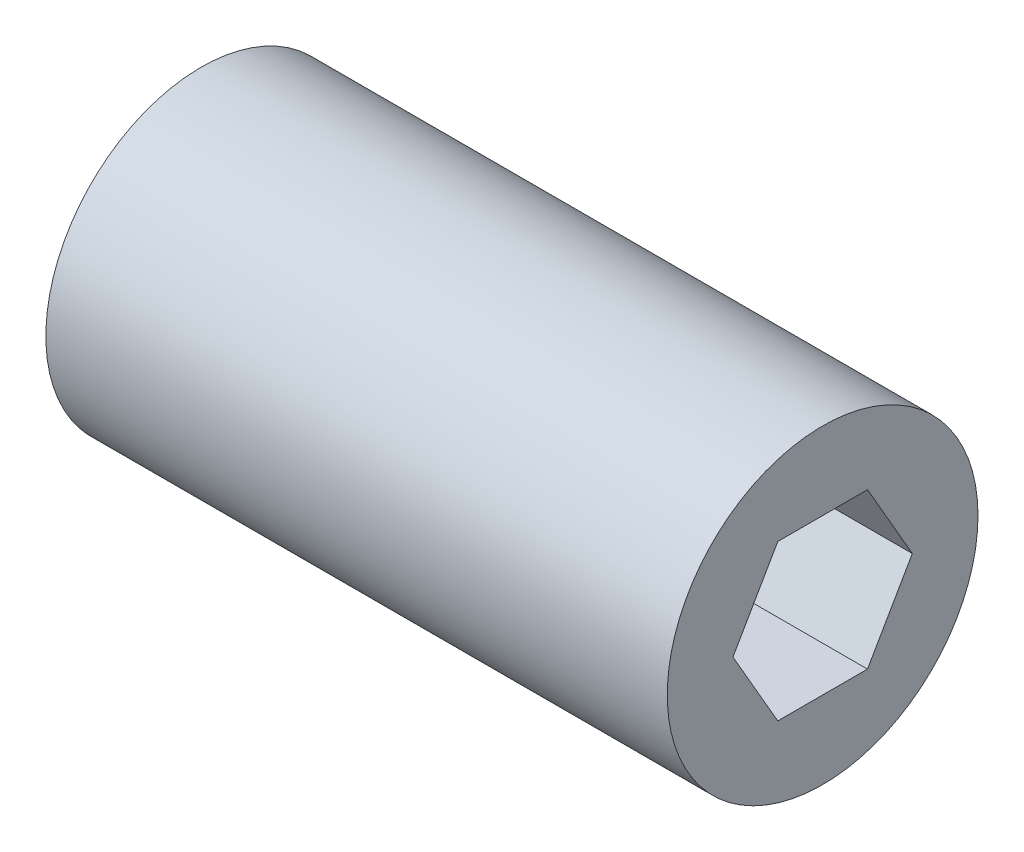
SolidWorks part; units mm, degrees
material "PET"
ref_plane "Front" through (0, 0, 0) normal (0, 0, 1) x (1, 0, 0)
ref_plane "Top" through (0, 0, 0) normal (0, 1, 0) x (1, 0, 0)
ref_plane "Right" through (0, 0, 0) normal (1, 0, 0) x (0, 0, -1)
sketch "Sketch1" plane through (0, 0, 0) normal (1, 0, 0) x (0, 0, -1)
  line L1 (7.3323, 0) -> (3.6662, 6.35)
  line L2 (3.6662, 6.35) -> (-3.6662, 6.35)
  line L3 (-3.6662, 6.35) -> (-7.3323, 0)
  line L4 (-7.3323, 0) -> (-3.6662, -6.35)
  line L5 (-3.6662, -6.35) -> (3.6662, -6.35)
  line L6 (3.6662, -6.35) -> (7.3323, 0)
  circle A0 centre (0, 0) radius 6.35 construction
  circle A1 centre (0, 0) radius 12.7
  dimension "D2" = 25.4
  dimension "D1" = 12.7
extrude "Boss-Extrude1" add sketch "Sketch1" along normal mid plane 50.8
